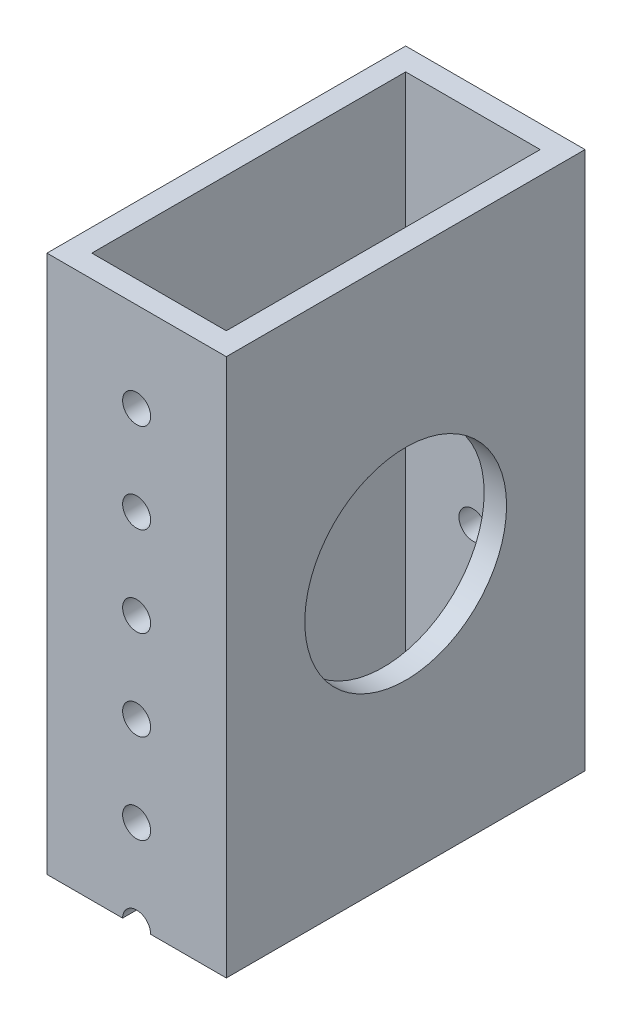
SolidWorks part; units mm, degrees
ref_plane "Front" through (0, 0, 0) normal (0, 0, 1) x (1, 0, 0)
ref_plane "Top" through (0, 0, 0) normal (0, 1, 0) x (1, 0, 0)
ref_plane "Right" through (0, 0, 0) normal (1, 0, 0) x (0, 0, -1)
sketch "Sketch1" plane through (0, 0, 0) normal (0, 1, 0) x (1, 0, 0)
  line L0 (-9.525, 22.225) -> (-9.525, -22.225)
  line L1 (-12.7, 25.4) -> (12.7, 25.4)
  line L2 (-12.7, 25.4) -> (-12.7, -25.4)
  line L3 (-12.7, -25.4) -> (12.7, -25.4)
  line L4 (12.7, 25.4) -> (12.7, -25.4)
  line L5 (-12.7, 25.4) -> (12.7, -25.4) construction
  line L6 (-12.7, -25.4) -> (12.7, 25.4) construction
  line L7 (-9.525, -22.225) -> (9.525, -22.225)
  line L8 (9.525, 22.225) -> (9.525, -22.225)
  line L9 (-9.525, 22.225) -> (9.525, 22.225)
  point P0 (0, 0)
  dimension "D1" = 25.4
  dimension "D2" = 50.8
  dimension "D3" = 3.175
extrude "Boss-Extrude1" add sketch "Sketch1" along normal mid plane 76.2
hole_wizard "5/32 (0.15625) Diameter Hole1" positions "Sketch3" profile "Sketch4" hole size "5/32" standard "ANSI Inch" end condition through all
sketch "Sketch3" plane through (0, 0, -25.4) normal (0, 0, -1) x (-1, 0, 0)
  line L0 (-12.7, 38.1) -> (12.7, 38.1) construction
  line L1 (0, 25.4) -> (0, 38.1) construction
  point P0 (0, 25.4)
  point P5 (0, 38.1)
  point P19 (0, 12.7)
  point P20 (0, 0)
  point P21 (0, -12.7)
  point P22 (0, -25.4)
  point P23 (0, -38.1)
  point P24 (0, -50.8)
  point P25 (0, -63.5)
  point P26 (0, -76.2)
  point P27 (0, -88.9)
  point P28 (0, -101.6)
  point P29 (0, -114.3)
  point P30 (0, -127)
  point P31 (0, -139.7)
  point P32 (0, -152.4)
  point P33 (0, -165.1)
  point P34 (0, -177.8)
  point P35 (0, -190.5)
  point P36 (0, -203.2)
  point P37 (0, -215.9)
  point P38 (0, -228.6)
  point P39 (0, -241.3)
  point P40 (0, -254)
  point P41 (0, -266.7)
  point P42 (0, -279.4)
  point P43 (0, -292.1)
  point P44 (0, -304.8)
  point P45 (0, -317.5)
  point P46 (0, -330.2)
  point P47 (0, -342.9)
  point P48 (0, -355.6)
  point P49 (0, -368.3)
  point P50 (0, -381)
  point P51 (0, -393.7)
  point P52 (0, -406.4)
  point P53 (0, -419.1)
  point P54 (0, -431.8)
  point P55 (0, -444.5)
  point P56 (0, -457.2)
  point P57 (0, -469.9)
  point P58 (0, -482.6)
  point P59 (0, -495.3)
  point P60 (0, -508)
  point P61 (0, -520.7)
  point P62 (0, -533.4)
  point P63 (0, -546.1)
  point P64 (0, -558.8)
  point P65 (0, -571.5)
  point P66 (0, -584.2)
  point P67 (0, -596.9)
  point P68 (0, -609.6)
  point P69 (0, -622.3)
  point P70 (0, -635)
  point P71 (0, -647.7)
  point P72 (0, -660.4)
  point P73 (0, -673.1)
  point P74 (0, -685.8)
  point P75 (0, -698.5)
  point P76 (0, -711.2)
  point P77 (0, -723.9)
  point P78 (0, -736.6)
  point P79 (0, -749.3)
  point P80 (0, -762)
  point P81 (0, -774.7)
  point P82 (0, -787.4)
  point P83 (0, -800.1)
  point P84 (0, -812.8)
  point P85 (0, -825.5)
  point P86 (0, -838.2)
  dimension "D1" = 12.7
  dimension "D2" = 69
sketch "Sketch4" plane through (0, 25.4, -25.4) normal (1, 0, 0) x (0, 1, 0)
  line L0 (0, 0) -> (0, 50.8)
  line L1 (0, 50.8) -> (1.9844, 50.8)
  line L2 (1.9844, 50.8) -> (1.9844, 0)
  line L5 (1.9844, 0) -> (0, 0)
  line L11 (0, -6.35) -> (0, 107.95) construction
  dimension "Thru Hole Dia." = 3.9688
  dimension "Thru Hole Depth" = 50.8
sketch "Sketch5" plane through (12.7, 0, 0) normal (1, 0, 0) x (0, 0, -1)
  circle A0 centre (0, 0) radius 14.2875
  dimension "D1" = 28.575
extrude "Cut-Extrude1" cut sketch "Sketch5" against normal through all
